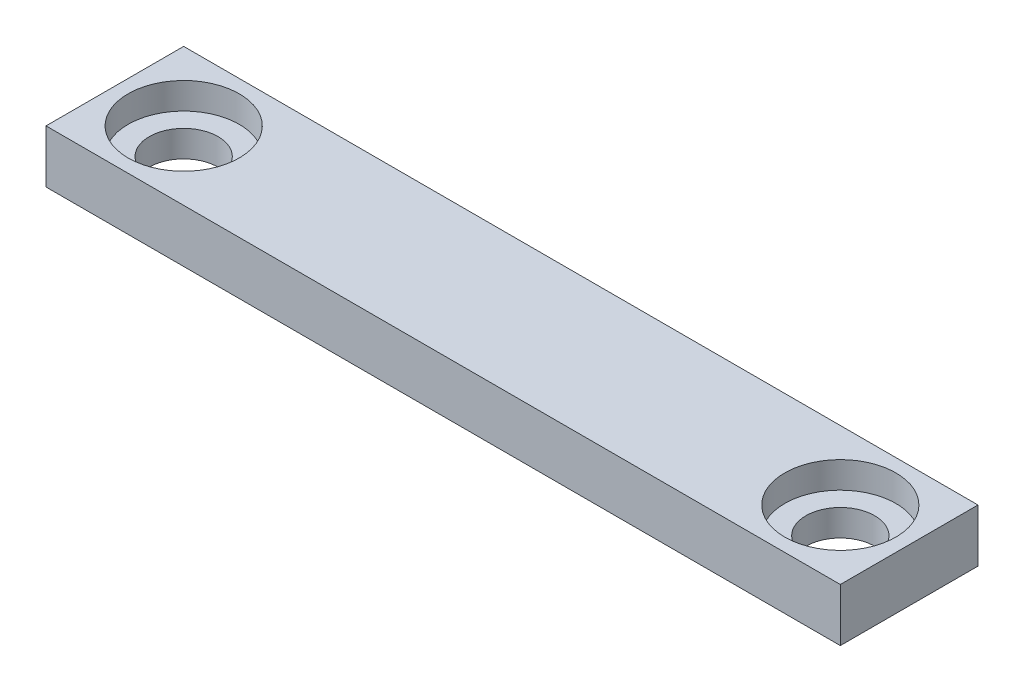
SolidWorks part; units mm, degrees
ref_plane "Front Plane" through (0, 0, 0) normal (0, 0, 1) x (1, 0, 0)
ref_plane "Top Plane" through (0, 0, 0) normal (0, 1, 0) x (1, 0, 0)
ref_plane "Right Plane" through (0, 0, 0) normal (1, 0, 0) x (0, 0, -1)
sketch "Sketch1" plane through (0, 0, 0) normal (0, 1, 0) x (1, 0, 0)
  line L1 (0, 0) -> (19.05, 0)
  line L2 (0, 0) -> (0, 3.302)
  line L3 (0, 3.302) -> (19.05, 3.302)
  line L4 (19.05, 0) -> (19.05, 3.302)
extrude "Boss-Extrude1" add sketch "Sketch1" along normal blind 1.27
hole_wizard "CBORE for #00 Binding Head Machine Screw1" positions "Sketch3" profile "Sketch2" counterbore size "#00" standard "ANSI Inch" end condition through all
sketch "Sketch3" plane through (0, 1.27, 0) normal (0, 1, 0) x (1, 0, 0)
  point P0 (1.651, 1.651)
sketch "Sketch2" plane through (1.651, 1.27, -1.651) normal (1, 0, 0) x (0, 0, 1)
  line L0 (0, 0) -> (0, 1.27)
  line L1 (0, 1.27) -> (0.8255, 1.27)
  line L3 (0.8255, 1.27) -> (0.8255, 0.635)
  line L4 (0.8255, 0.635) -> (1.3335, 0.635)
  line L5 (1.3335, 0.635) -> (1.3335, 0)
  line L7 (1.3335, 0) -> (0, 0)
  line L11 (0, -6.35) -> (0, 107.95) construction
  dimension "Thru Hole Dia." = 1.651
  dimension "Thru Hole Depth" = 1.27
  dimension "C'Bore Dia." = 2.667
  dimension "C'Bore Depth" = 0.635
ref_plane "Plane1" through (9.525, 0, 0) normal (-1, 0, 0) x (0, 0, 1)
mirror "Mirror1" about plane through (9.525, 0, 0) normal (-1, 0, 0) of "CBORE for #00 Binding Head Machine Screw1"
